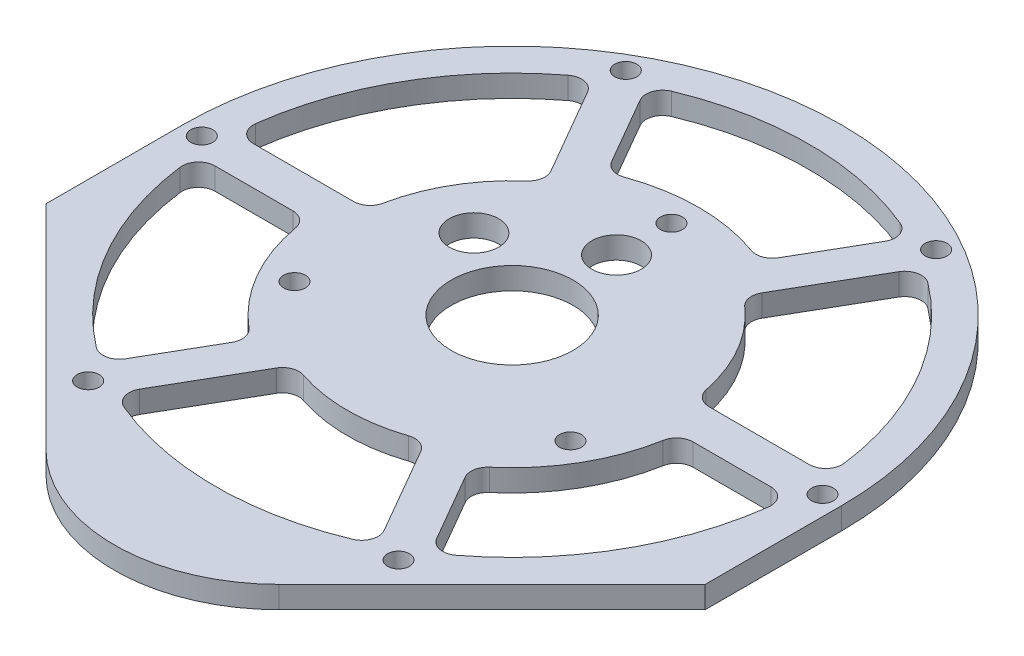
SolidWorks part; units mm, degrees
material "Thornel Mat VMA"
ref_plane "前视基准面" through (0, 0, 0) normal (0, 0, 1) x (1, 0, 0)
ref_plane "上视基准面" through (0, 0, 0) normal (0, 1, 0) x (1, 0, 0)
ref_plane "右视基准面" through (0, 0, 0) normal (1, 0, 0) x (0, 0, -1)
sketch "草图1" plane through (0, 0, 0) normal (0, 1, 0) x (1, 0, 0)
  line L0 (-60, -24.8528) -> (-21.2132, -63.6396)
  line L5 (-60, 0) -> (-60, -24.8528)
  line L6 (0, -55) -> (0, 55) construction
  line L7 (60, -24.8528) -> (21.2132, -63.6396)
  line L8 (60, 0) -> (60, -24.8528)
  line L9 (0, 29) -> (0, 0) construction
  line L10 (0, 0) -> (-22.8483, 13.1915) construction
  circle A0 centre (0, 0) radius 56.5 construction
  arc A1 (60, 0) -> (-60, 0) centre (0, 0) ccw
  circle A2 centre (-28.25, 48.9304) radius 2
  circle A3 centre (28.25, 48.9304) radius 2
  circle A4 centre (56.5, 0) radius 2
  circle A5 centre (28.25, -48.9304) radius 2
  circle A6 centre (0, 0) radius 11.1
  circle A7 centre (-28.25, -48.9304) radius 2
  circle A8 centre (-56.5, 0) radius 2
  circle A9 centre (0, 0) radius 29 construction
  circle A10 centre (0, 29) radius 2
  circle A11 centre (25.1147, -14.5) radius 2
  circle A12 centre (-25.1147, -14.5) radius 2
  arc A13 (-21.2132, -63.6396) -> (21.2132, -63.6396) centre (0, -42.4264) ccw
  circle A15 centre (0, 19) radius 4.5
  circle A16 centre (0, 0) radius 19 construction
  circle A17 centre (-16.4545, 9.5) radius 4.5
  dimension "D1" = 22.2
  dimension "D2" = 4
  dimension "D3" = 58
  dimension "D4" = 113
  dimension "D6" = 4
  dimension "D7" = 120
  dimension "D8" = 30
  dimension "D9" = 38
  dimension "D10" = 9
  dimension "D11" = 60
  dimension "D5" = 6
extrude "凸台-拉伸1" add sketch "草图1" along normal blind 4
sketch "草图2" plane through (0, 4, 0) normal (0, 1, 0) x (1, 0, 0)
  line L0 (-29.9743, 44.917) -> (-17.9287, 24.0533)
  line L1 (-53.8865, 3.5) -> (-29.7951, 3.5)
  line L2 (0, 0) -> (-28.25, 48.9304) construction
  line L3 (0, 0) -> (-56.5, 0) construction
  line L4 (23.9121, 48.417) -> (13.8786, 31.0384)
  line L5 (-23.9121, 48.417) -> (-13.8786, 31.0384)
  line L6 (53.8865, 3.5) -> (29.7951, 3.5)
  line L7 (29.9743, 44.917) -> (17.9287, 24.0533)
  line L8 (29.9743, -44.917) -> (19.9408, -27.5384)
  line L9 (53.8865, -3.5) -> (33.8194, -3.5)
  line L10 (-23.9121, -48.417) -> (-11.8665, -27.5533)
  line L11 (23.9121, -48.417) -> (11.8665, -27.5533)
  line L12 (-53.8865, -3.5) -> (-33.8194, -3.5)
  line L13 (-29.9743, -44.917) -> (-19.9408, -27.5384)
  arc A0 (-17.9287, 24.0533) -> (-29.7951, 3.5) centre (0, 0) ccw
  arc A1 (-29.9743, 44.917) -> (-53.8865, 3.5) centre (0, 0) ccw
  arc A2 (60, 0) -> (-60, 0) centre (0, 0) ccw construction
  arc A3 (23.9121, 48.417) -> (-23.9121, 48.417) centre (0, 0) ccw
  arc A5 (53.8865, 3.5) -> (29.9743, 44.917) centre (0, 0) ccw
  arc A6 (29.7951, 3.5) -> (17.9287, 24.0533) centre (0, 0) ccw
  arc A7 (-13.8786, 31.0384) -> (13.8786, 31.0384) centre (0, 0) cw
  arc A8 (11.8665, 27.5533) -> (-11.8665, 27.5533) centre (0, 0) ccw [skipped]
  arc A9 (29.9743, -44.917) -> (53.8865, -3.5) centre (0, 0) ccw
  arc A11 (-23.9121, -48.417) -> (23.9121, -48.417) centre (0, 0) ccw
  arc A12 (-11.8665, -27.5533) -> (11.8665, -27.5533) centre (0, 0) ccw
  arc A13 (-53.8865, -3.5) -> (-29.9743, -44.917) centre (0, 0) ccw
  arc A15 (17.9287, -24.0533) -> (29.7951, -3.5) centre (0, 0) ccw [skipped]
  arc A16 (-29.7951, -3.5) -> (-17.9287, -24.0533) centre (0, 0) ccw [skipped]
  arc A17 (33.8194, -3.5) -> (19.9408, -27.5384) centre (0, 0) cw
  arc A18 (-19.9408, -27.5384) -> (-33.8194, -3.5) centre (0, 0) cw
  point P46 (34.9309, -8.6196)
  point P47 (37.7422, -3.5)
  dimension "D1" = 30
  dimension "D2" = 6
  dimension "D6" = 34
  dimension "D3" = 3.5
  dimension "D4" = 3.5
  dimension "D5" = 6
extrude "切除-拉伸1" cut sketch "草图2" against normal through all
fillet "圆角2" radius 3 24 edges at (-17.9287, 2, -24.0533) (-29.7951, 2, -3.5) (-53.8865, 2, -3.5) (29.7951, 2, -3.5) (17.9287, 2, -24.0533) (29.9743, 2, -44.917) (53.8865, 2, -3.5) (-23.9121, 2, -48.417) (23.9121, 2, -48.417) (13.8786, 2, -31.0384) (-13.8786, 2, -31.0384) (-29.9743, 2, -44.917) (-19.9408, 2, 27.5384) (-29.9743, 2, 44.917) (-53.8865, 2, 3.5) (53.8865, 2, 3.5) (29.9743, 2, 44.917) (19.9408, 2, 27.5384) (33.8194, 2, 3.5) (-11.8665, 2, 27.5533) (11.8665, 2, 27.5533) (23.9121, 2, 48.417) (-23.9121, 2, 48.417) (-33.8194, 2, 3.5)
